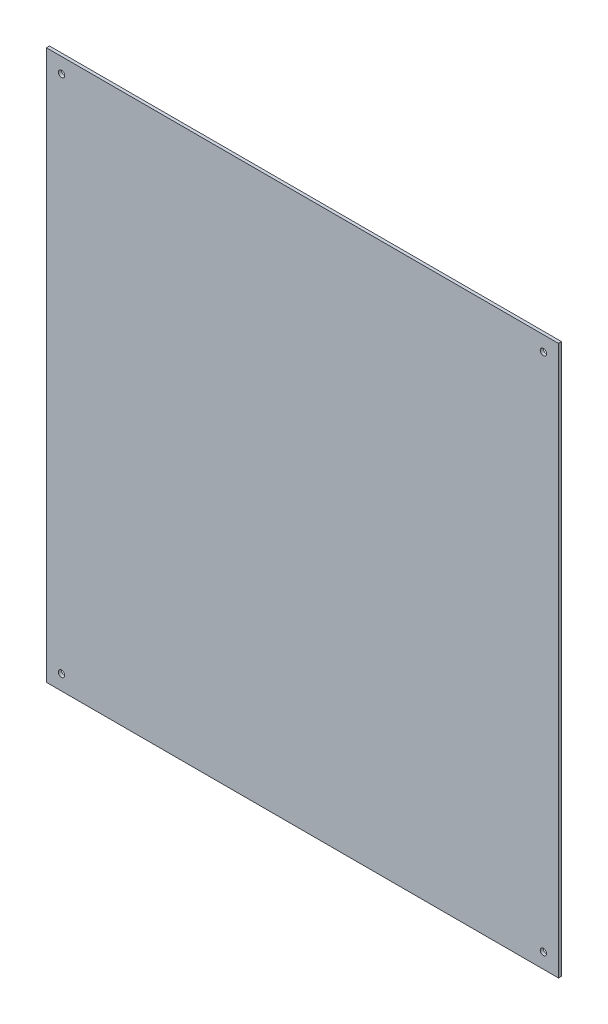
SolidWorks part; units mm, degrees
material "6061-T6 (SS)"
ref_plane "Front Plane" through (0, 0, 0) normal (0, 0, 1) x (1, 0, 0)
ref_plane "Top Plane" through (0, 0, 0) normal (0, 1, 0) x (1, 0, 0)
ref_plane "Right Plane" through (0, 0, 0) normal (1, 0, 0) x (0, 0, -1)
sketch "Sketch1" plane through (0, 0, 0) normal (0, 0, 1) x (1, 0, 0)
  line L0 (-170, 182.5) -> (170, 182.5)
  line L1 (170, 182.5) -> (170, -182.5)
  line L2 (170, -182.5) -> (-170, -182.5)
  line L3 (-170, -182.5) -> (-170, 182.5)
  line L4 (-170, 182.5) -> (170, -182.5) construction
  circle A0 centre (-160, -172.5) radius 2.1
  circle A1 centre (160, -172.5) radius 2.1
  circle A2 centre (160, 172.5) radius 2.1
  circle A3 centre (-160, 172.5) radius 2.1
  dimension "D3" = 10
  dimension "D4" = 10
  dimension "D5" = 4.2
  dimension "D6" = 10
  dimension "D7" = 10
  dimension "D1" = 340
  dimension "D2" = 365
extrude "Boss-Extrude1" add sketch "Sketch1" along normal blind 2.032
